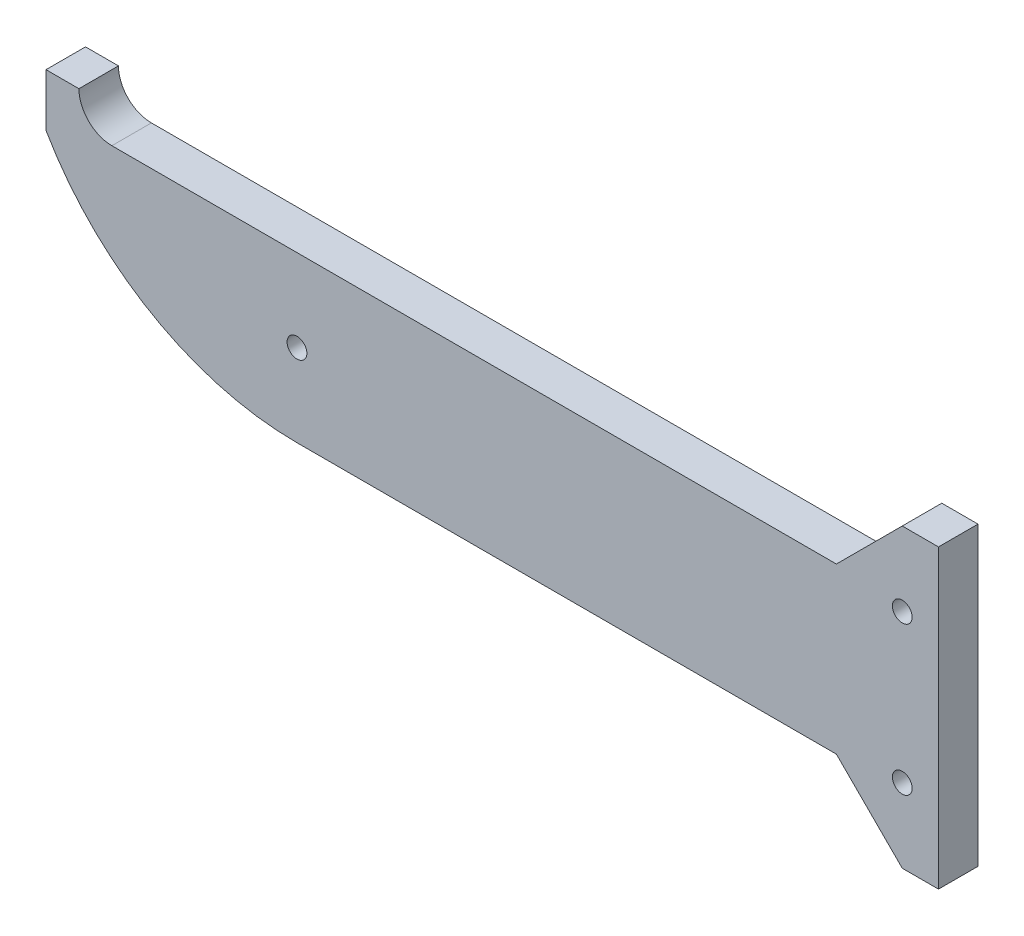
SolidWorks part; units mm, degrees
ref_plane "Front Plane" through (0, 0, 0) normal (0, 0, 1) x (1, 0, 0)
ref_plane "Top Plane" through (0, 0, 0) normal (0, 1, 0) x (1, 0, 0)
ref_plane "Right Plane" through (0, 0, 0) normal (1, 0, 0) x (0, 0, -1)
sketch "Sketch1" plane through (0, 0, 0) normal (0, 0, 1) x (1, 0, 0)
  line L0 (0, -3) -> (120, -3) construction
  line L1 (120, -25) -> (38.1051, -25)
  line L2 (120, -3) -> (130, 10) construction
  line L3 (130, 10) -> (135.5, 10)
  line L4 (135.5, 10) -> (135.5, -35)
  line L5 (135.5, -35) -> (130, -35)
  line L6 (130, -35) -> (120, -25)
  line L7 (120, -3) -> (120, -25) construction
  line L8 (130, 10) -> (130, -35) construction
  line L9 (10, 0) -> (120, 0)
  line L10 (120, 0) -> (120, -3) construction
  line L11 (0, 0) -> (0, -3)
  line L12 (0, 0) -> (0, 5)
  line L13 (0, 5) -> (5, 5)
  line L14 (120, 0) -> (130, 10)
  line L15 (135.5, 10) -> (151.5, 10) construction
  line L16 (151.5, 10) -> (151.5, -7.5) construction
  line L17 (151.5, -7.5) -> (145.5, -7.5) construction
  line L18 (145.5, -7.5) -> (145.5, -1.5) construction
  line L19 (145.5, -1.5) -> (138.5, -1.5) construction
  line L20 (138.5, -1.5) -> (138.5, -17.5) construction
  line L21 (138.5, -17.5) -> (151.5, -17.5) construction
  line L22 (151.5, -17.5) -> (151.5, -35) construction
  line L23 (151.5, -35) -> (145.5, -35) construction
  line L24 (145.5, -35) -> (145.5, -29) construction
  line L25 (145.5, -29) -> (138.5, -29) construction
  line L26 (138.5, -29) -> (138.5, -35) construction
  line L27 (138.5, -35) -> (135.5, -35) construction
  line L28 (38.1051, -25) -> (38.1051, 0) construction
  arc A0 (0, -3) -> (38.1051, -25) centre (38.1051, 19) ccw
  arc A1 (5, 5) -> (10, 0) centre (10, 5) ccw
  circle A2 centre (130, -1.25) radius 1.5
  circle A3 centre (130, -23.75) radius 1.5
  circle A4 centre (38.1051, -12.5) radius 1.5
  dimension "D13" = 3
  dimension "D1" = 22
  dimension "D2" = 44
  dimension "D6" = 5.5
  dimension "D3" = 45
  dimension "D4" = 45
  dimension "D5" = 3
  dimension "D7" = 45
  dimension "D8" = 5
  dimension "D9" = 5
  dimension "D10" = 110
  dimension "D11" = 11.25
  dimension "D12" = 11.25
  dimension "D14" = 17.5
  dimension "D15" = 6
  dimension "D16" = 6
  dimension "D17" = 7
  dimension "D18" = 3
extrude "Boss-Extrude1" add sketch "Sketch1" along normal blind 6
equation "\"D11@Sketch1\"=\"D3@Sketch1\"/4"
equation "\"D12@Sketch1\"=\"D11@Sketch1\""
equation "\"M3_d\"= \"M3_d@filament_spool_holder.Assembly\""
equation "\"D13@Sketch1\"=\"M3_d\""
equation "\"spool_holder_l\"= \"spool_holder_l@filament_spool_holder.Assembly\""
equation "\"D10@Sketch1\"=\"spool_holder_l\""
equation "\"housing_t\"= \"housing_t@filament_spool_holder.Assembly\""
equation "\"D1@Boss-Extrude1\"=\"housing_t\""
equation "\"D17@Sketch1\"=\"housing_t\" + 1"
equation "\"D15@Sketch1\"=\"housing_t\""
